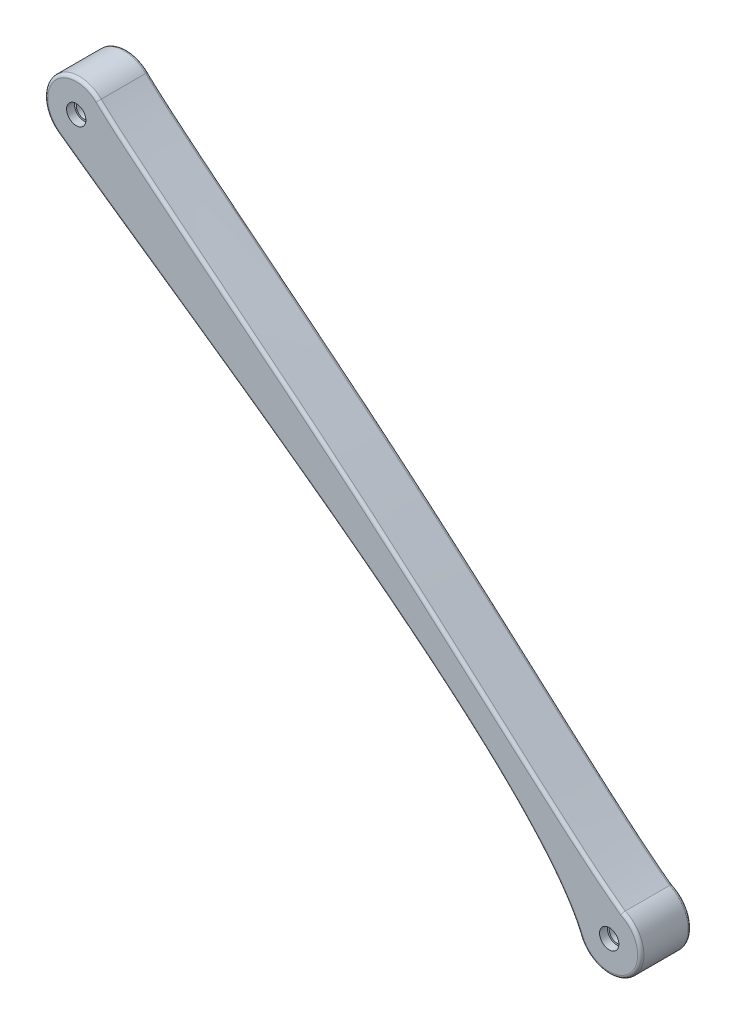
SolidWorks part; units mm, degrees
ref_plane "Front Plane" through (0, 0, 0) normal (0, 0, 1) x (1, 0, 0)
ref_plane "Top Plane" through (0, 0, 0) normal (0, 1, 0) x (1, 0, 0)
ref_plane "Right Plane" through (0, 0, 0) normal (1, 0, 0) x (0, 0, -1)
sketch "Sketch1" plane through (0, 0, 0) normal (0, 0, 1) x (1, 0, 0)
  line L0 (0, 0) -> (380.5095, 0) construction
  line L1 (0, 0) -> (168.5298, -141.4133) construction
  circle A0 centre (0, 0) radius 10
  circle A1 centre (168.5298, -141.4133) radius 10
  arc A2 (177.5369, -137.0691) -> (161.536, -134.2658) centre (168.5298, -141.4133) ccw construction
  circle A3 centre (-5.1771, -29.5503) radius 21.5 construction
  spline S0 degree 3 poles (-5.9151, -8.063) (34.7182, -37.8721) (143.5155, -107.1437) (159.2906, -145.2392) knots 0 0 0 0 1 1 1 1
  spline S1 degree 3 poles (6.9324, 7.2071) (17.2443, -2.7118) (60.2271, -35.9313) (124.7504, -90.3801) (157.2481, -121.2241) (172.6319, -132.2934) knots 0 0 0 0 0.399024 0.499024 1 1 1 1
  dimension "D3" = 20
  dimension "D4" = 20
  dimension "D1" = 220
  dimension "D2" = 40
extrude "Boss-Extrude1" add sketch "Sketch1" along normal blind 8 contours A0 | S1 A0 S0 A1 | A1
sketch "Sketch2" plane through (0, 0, 8) normal (0, 0, 1) x (1, 0, 0)
  circle A0 centre (0, 0) radius 3.05
  circle A1 centre (168.5298, -141.4133) radius 3.05
  dimension "D1" = 6.1
  dimension "D2" = 6.1
extrude "Cut-Extrude1" cut sketch "Sketch2" against normal blind 2.5
sketch "Sketch3" plane through (0, 0, 8) normal (0, 0, 1) x (1, 0, 0)
  circle A0 centre (0, 0) radius 2.5
  circle A1 centre (168.5298, -141.4133) radius 2.5
  dimension "D1" = 5
  dimension "D2" = 5
extrude "Cut-Extrude2" cut sketch "Sketch3" against normal through all
mirror "Mirror1" about plane through (0, 0, 0) normal (0, 0, 1) of "Cut-Extrude2", "Cut-Extrude1", "Boss-Extrude1"
fillet "Fillet1" radius 1 8 edges at (175.4937, -148.5899, 8) (-7.652, 6.438, -8) (175.4937, -148.5899, -8) (-7.652, 6.438, 8)
